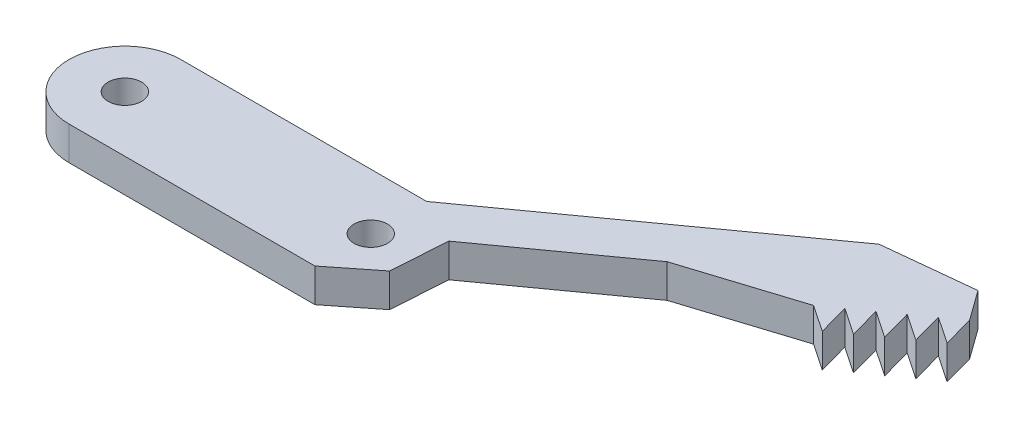
SolidWorks part; units mm, degrees
ref_plane "Ön Düzlem" through (0, 0, 0) normal (0, 0, 1) x (1, 0, 0)
ref_plane "Üst Düzlem" through (0, 0, 0) normal (0, 1, 0) x (1, 0, 0)
ref_plane "Sağ Düzlem" through (0, 0, 0) normal (1, 0, 0) x (0, 0, -1)
sketch "Çizim2" plane through (0, 0, 0) normal (0, 1, 0) x (1, 0, 0)
  line L0 (-11, 0) -> (-9.5, 0) construction
  line L1 (-11, 5) -> (11, 5)
  line L2 (-11, -5) -> (11, -5)
  line L3 (9.5, 0) -> (11, 0) construction
  circle A0 centre (-11, 0) radius 1.5
  arc A1 (-11, 5) -> (-11, -5) centre (-11, 0) ccw
  circle A2 centre (11, 0) radius 1.5
  arc A3 (11, -5) -> (11, 5) centre (11, 0) ccw
  point P4 (0, 0)
  dimension "D1" = 10
  dimension "D2" = 10
  dimension "D3" = 3
  dimension "D4" = 3
  dimension "D5" = 22
extrude "Yükseklik-Ekstrüzyon1" add sketch "Çizim2" along normal blind 3
sketch "Çizim3" plane through (0, 3, 0) normal (0, 1, 0) x (1, 0, 0)
  line L0 (11, 5) -> (40.2335, 26.0096)
  line L1 (40.2335, 26.0096) -> (46.0695, 17.8892)
  line L2 (-11, -5) -> (11, -5)
  line L3 (11, 5) -> (-11, 5)
  line L6 (46.0695, 17.8892) -> (37.9491, 12.0532)
  line L7 (37.9491, 12.0532) -> (36.3694, 14.2512)
  line L8 (36.3694, 14.2512) -> (26.4288, 11.0884)
  line L9 (26.4288, 11.0884) -> (15.0602, 2.918)
  arc A2 (-11, 5) -> (-11, -5) centre (-11, 0) ccw
  arc A3 (11, -5) -> (11, 5) centre (11, 0) ccw
  arc A5 (15.0602, 2.918) -> (11, 5) centre (11, 0) ccw
  dimension "D2" = 36
  dimension "D3" = 10
  dimension "D4" = 10
  dimension "D5" = 14
  dimension "D1" = 0
extrude "Yükseklik-Ekstrüzyon2" add sketch "Çizim3" against normal blind 3
sketch "Çizim4" plane through (0, 3, 0) normal (0, 1, 0) x (1, 0, 0)
  line L7 (34.5492, 21.9244) -> (40.2335, 26.0096)
  line L8 (40.2335, 26.0096) -> (11, 5) construction
  line L9 (40.2335, 26.0096) -> (42.5679, 22.7615)
  line L10 (46.0695, 17.8892) -> (40.2335, 26.0096) construction
  line L11 (42.5679, 22.7615) -> (34.5492, 21.9244)
  dimension "D1" = 7
  dimension "D2" = 4
extrude "Kes-Ekstrüzyon1" cut sketch "Çizim4" against normal blind 3
sketch "Çizim5" plane through (0, 3, 0) normal (0, 1, 0) x (1, 0, 0)
  line L0 (36.3694, 14.2512) -> (44.4898, 20.0872) construction
  line L1 (46.0695, 17.8892) -> (42.5679, 22.7615) construction
  line L2 (36.3694, 14.2512) -> (38.7611, 12.6368)
  line L3 (37.9491, 12.0532) -> (46.0695, 17.8892) construction
  line L4 (38.7611, 12.6368) -> (37.9935, 15.4184)
  line L5 (37.9935, 15.4184) -> (40.3852, 13.804)
  line L6 (40.3852, 13.804) -> (39.6176, 16.5856)
  line L7 (39.6176, 16.5856) -> (42.0093, 14.9712)
  line L8 (42.0093, 14.9712) -> (41.2417, 17.7528)
  line L9 (41.2417, 17.7528) -> (43.6333, 16.1384)
  line L10 (43.6333, 16.1384) -> (42.8658, 18.92)
  line L11 (42.8658, 18.92) -> (45.2574, 17.3056)
  line L12 (45.2574, 17.3056) -> (44.4898, 20.0872)
  line L13 (36.3694, 14.2512) -> (37.9491, 12.0532)
  line L14 (37.9491, 12.0532) -> (46.0695, 17.8892)
  line L15 (46.0695, 17.8892) -> (44.4898, 20.0872)
  line M12 (36.3694, 14.2512) -> (37.9491, 12.0532)
  line M13 (37.9491, 12.0532) -> (46.0695, 17.8892)
  line M14 (46.0695, 17.8892) -> (42.5679, 22.7615)
  dimension "D1" = 2
  dimension "D2" = 5
extrude "Kes-Ekstrüzyon2" cut sketch "Çizim5" against normal blind 3 contours L2 M12 M13 | L5 L4 M13 | L7 L6 M13 | L9 L8 M13 | L11 L10 M13 | L12 M13 M14
sketch "Çizim6" plane through (0, 3, 0) normal (0, 1, 0) x (1, 0, 0)
  line L0 (15.0602, 2.918) -> (14.7368, -2.0412)
  line L1 (14.7368, -2.0412) -> (11, -5)
  line L2 (11, -5) -> (11, -9.8078)
  line L3 (11, -9.8078) -> (27.6902, -9.8078)
  line L4 (27.6902, -9.8078) -> (28.885, 0.6739)
  line L5 (28.885, 0.6739) -> (15.0602, 2.918)
extrude "Kes-Ekstrüzyon3" cut sketch "Çizim6" against normal blind 3
